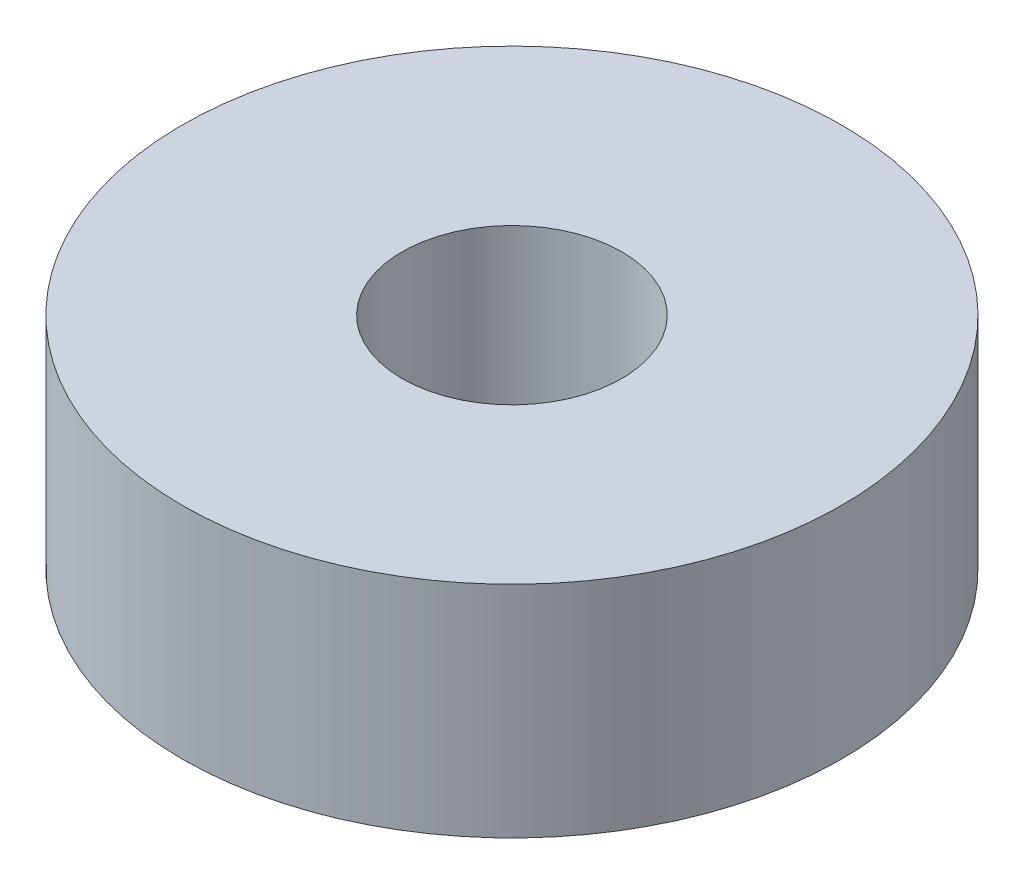
SolidWorks part; units mm, degrees
ref_plane "前视基准面" through (0, 0, 0) normal (0, 0, 1) x (1, 0, 0)
ref_plane "上视基准面" through (0, 0, 0) normal (0, 1, 0) x (1, 0, 0)
ref_plane "右视基准面" through (0, 0, 0) normal (1, 0, 0) x (0, 0, -1)
sketch "Sketch1" plane through (0, 0, 0) normal (0, 1, 0) x (1, 0, 0)
  circle A0 centre (0, 0) radius 2
  circle A1 centre (0, 0) radius 6
  dimension "D1" = 4
  dimension "D2" = 12
extrude "Boss-Extrude1" add sketch "Sketch1" along normal blind 4
